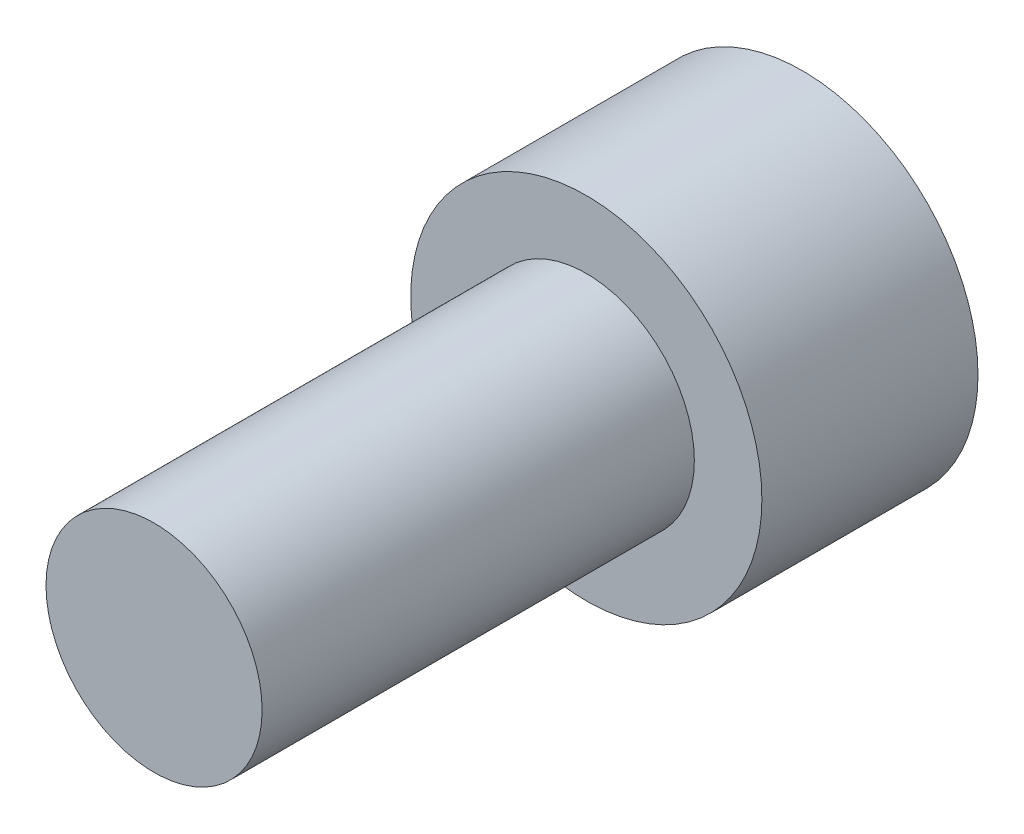
SolidWorks part; units mm, degrees
material "Alloy Steel"
ref_plane "Front Plane" through (0, 0, 0) normal (0, 0, 1) x (1, 0, 0)
ref_plane "Top Plane" through (0, 0, 0) normal (0, 1, 0) x (1, 0, 0)
ref_plane "Right Plane" through (0, 0, 0) normal (1, 0, 0) x (0, 0, -1)
sketch "Sketch1" plane through (0, 0, 0) normal (0, 0, 1) x (1, 0, 0)
  circle A0 centre (0, 0) radius 6.5
  dimension "D1" = 13
extrude "Boss-Extrude1" add sketch "Sketch1" along normal blind 8
sketch "Sketch2" plane through (0, 0, 8) normal (0, 0, 1) x (1, 0, 0)
  circle A0 centre (0, 0) radius 4
  dimension "D1" = 8
extrude "Boss-Extrude2" add sketch "Sketch2" along normal blind 16
